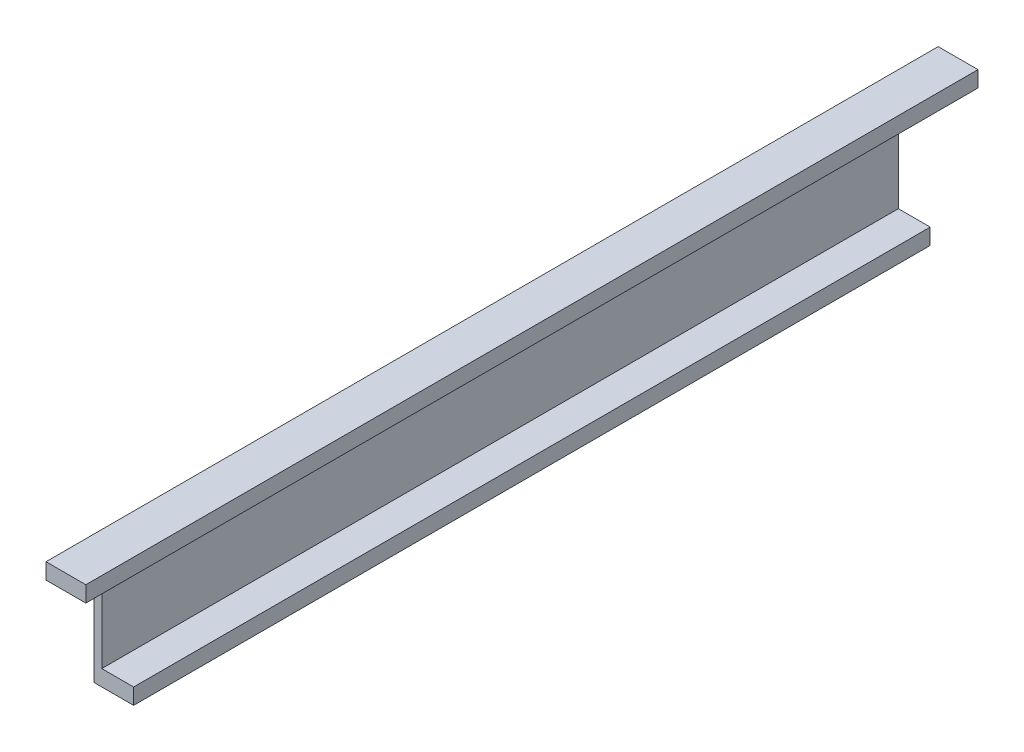
SolidWorks part; units mm, degrees
material "ABS PC"
ref_plane "Alzado" through (0, 0, 0) normal (0, 0, 1) x (1, 0, 0)
ref_plane "Planta" through (0, 0, 0) normal (0, 1, 0) x (1, 0, 0)
ref_plane "Vista lateral" through (0, 0, 0) normal (1, 0, 0) x (0, 0, -1)
sketch "Croquis1" plane through (0, 0, 0) normal (1, 0, 0) x (0, 0, -1)
  line L0 (-110, 24.5) -> (-110, 15) construction
  line L1 (125, -2.5) -> (-125, -2.5)
  line L2 (125, -2.5) -> (125, 2.5)
  line L3 (125, 2.5) -> (-97, 2.5)
  line L4 (-125, -2.5) -> (-125, 2.5)
  line L5 (125, -2.5) -> (0, 0) construction
  line L6 (125, 2.5) -> (-125, -2.5) construction
  line L7 (-117, 17.5) -> (-123, 2.5)
  line L8 (-103, 17.5) -> (-97, 2.5)
  line L9 (-123, 2.5) -> (-125, 2.5)
  circle A0 centre (-110, 17.5) radius 2.5
  arc A1 (-103, 17.5) -> (-117, 17.5) centre (-110, 17.5) ccw
  point P0 (0, 0)
  dimension "D1" = 250
  dimension "D3" = 5
  dimension "D4" = 14
  dimension "D2" = 5
  dimension "D5" = 15
  dimension "D6" = 15
  dimension "D7" = 2
extrude "Saliente-Extruir1" add sketch "Croquis1" along normal mid plane 2.5
sketch "Croquis5" plane through (1.25, 0, 0) normal (1, 0, 0) x (0, 0, -1)
  line L5 (-117, 17.5) -> (-123, 2.5)
  line L6 (-123, 2.5) -> (-125, 2.5)
  line L7 (-125, -2.5) -> (125, -2.5)
  line L8 (125, -2.5) -> (125, 2.5)
  line L9 (-97, 2.5) -> (-103, 17.5)
  line L10 (-117, 17.5) -> (-123, 2.5)
  line L12 (-125, -2.5) -> (125, -2.5)
  line L14 (-97, 2.5) -> (-103, 17.5)
  line L16 (-123, 2.5) -> (-125, 2.5)
  line L17 (-125, 2.5) -> (-125, -2.5)
  line L18 (-125, 2.5) -> (-125, -2.5)
  line L20 (125, -2.5) -> (125, 2.5)
  line L21 (125, 2.5) -> (-97, 2.5)
  line L22 (125, 2.5) -> (-97, 2.5)
  circle A0 centre (-110, 17.5) radius 12.5
  arc A1 (-103, 17.5) -> (-117, 17.5) centre (-110, 17.5) ccw
  arc A2 (-103, 17.5) -> (-117, 17.5) centre (-110, 17.5) ccw
  circle A3 centre (-110, 17.5) radius 15
  dimension "D2" = 25
  dimension "D3" = 30
  dimension "D1" = 0
extrude "Saliente-Extruir4" add sketch "Croquis5" against normal through all contours L14 A3 L10 A0
sketch "Croquis6" plane through (1.25, 0, 0) normal (1, 0, 0) x (0, 0, -1)
  circle A0 centre (-110, 17.5) radius 12.525
  dimension "D1" = 25.05
extrude "Cortar-Extruir3" cut sketch "Croquis6" against normal blind 10
sketch "Croquis7" plane through (0, 0, -125) normal (0, 0, -1) x (-1, 0, 0)
  line L0 (1.25, 32.8) -> (-1.25, 32.8)
  line L1 (1.25, -2.5) -> (3.75, -2.5)
  line L2 (1.25, -2.5) -> (1.25, 2.5) construction
  line L3 (-1.25, 2.5) -> (1.25, 2.5) construction
  line L4 (1.25, -2.5) -> (1.25, 2.5)
  line L5 (-1.25, 2.5) -> (1.25, 2.5)
  line L6 (1.25, 2.5) -> (1.25, 32.8)
  line L7 (1.25, 7.3619) -> (1.25, 32.5) construction
  line L9 (-1.25, 32.8) -> (-1.25, 37.8)
  line L10 (-1.25, 37.8) -> (3.75, 37.8)
  line L11 (3.75, 37.8) -> (3.75, -2.5)
  line M2 (1.25, -2.5) -> (1.25, 2.5)
  dimension "D1" = 30.3
  dimension "D2" = 5
  dimension "D3" = 2.5
extrude "Saliente-Extruir5" add sketch "Croquis7" against normal blind 200 contours L11 L10 L9 L0 L6 L1 M2
sketch "Croquis8" plane through (-1.25, 0, 0) normal (-1, 0, 0) x (0, 0, 1)
  line L0 (97, 2.5) -> (95, 2.5)
  line L1 (75, 2.5) -> (97, 2.5) construction
  line L2 (95, 2.5) -> (95, -2.5)
  line L3 (125, -2.5) -> (75, -2.5) construction
  line L11 (75, 2.5) -> (75, -2.5)
  line L12 (75, -2.5) -> (125, -2.5)
  line L13 (125, -2.5) -> (125, 2.5)
  line L14 (125, 2.5) -> (123, 2.5)
  line L15 (123, 2.5) -> (121.0552, 7.3619)
  line L16 (98.9448, 7.3619) -> (97, 2.5)
  line L17 (97, 2.5) -> (75, 2.5)
  line L18 (75, 2.5) -> (75, -2.5)
  line L19 (75, -2.5) -> (125, -2.5)
  line L20 (125, -2.5) -> (125, 2.5)
  line L21 (125, 2.5) -> (123, 2.5)
  line L22 (123, 2.5) -> (121.0552, 7.3619)
  line L23 (98.9448, 7.3619) -> (97, 2.5)
  line L24 (97, 2.5) -> (75, 2.5)
  circle A0 centre (110, 17.5) radius 12.525 construction
  arc A1 (121.0552, 7.3619) -> (98.9448, 7.3619) centre (110, 17.5) ccw
  arc A2 (121.0552, 7.3619) -> (98.9448, 7.3619) centre (110, 17.5) ccw
  circle A3 centre (110, 17.5) radius 12.525
  circle M2 centre (110, 17.5) radius 12.525
  line M4 (75, -2.5) -> (125, -2.5)
  line M5 (125, -2.5) -> (125, 2.5)
  line M6 (125, 2.5) -> (123, 2.5)
  line M7 (123, 2.5) -> (121.0552, 7.3619)
  arc M8 (121.0552, 7.3619) -> (98.9448, 7.3619) centre (110, 17.5) ccw
  line M9 (98.9448, 7.3619) -> (97, 2.5)
  line M10 (97, 2.5) -> (75, 2.5)
  dimension "D1" = 2
  dimension "D2" = 0
extrude "Saliente-Extruir6" add sketch "Croquis8" along normal blind 21 contours L2 M10 M4 M5 M6 M7 M8 M9 M2
sketch "Croquis10" plane through (0, 0, 75) normal (0, 0, 1) x (1, 0, 0)
  line L0 (1.25, 2.5) -> (1.25, 7.3619) construction
  line L1 (-22.25, 7.3619) -> (-22.25, 2.5) construction
  line L2 (-22.25, 2.5) -> (1.25, 2.5) construction
  line L3 (1.25, 2.5) -> (-22.25, 2.5) construction
  line L4 (-22.25, 2.5) -> (-22.25, -2.5) construction
  line L5 (-22.25, -2.5) -> (1.25, -2.5) construction
  line L6 (1.25, -2.5) -> (1.25, 2.5) construction
  line L7 (-3.75, 37.8) -> (-3.75, -2.5)
  line L8 (-3.75, -2.5) -> (-1.25, -2.5)
  line L9 (-1.25, -2.5) -> (-1.25, 2.5)
  line L10 (-1.25, 2.5) -> (-1.25, 32.8)
  line L11 (-1.25, 32.8) -> (1.25, 32.8)
  line L12 (1.25, 32.8) -> (1.25, 37.8)
  line L13 (1.25, 37.8) -> (-3.75, 37.8)
  line L14 (-3.75, 37.8) -> (-3.75, -2.5)
  line L15 (-3.75, -2.5) -> (-1.25, -2.5)
  line L16 (-1.25, -2.5) -> (-1.25, 2.5)
  line L17 (-1.25, 2.5) -> (-1.25, 32.8)
  line L18 (-1.25, 32.8) -> (1.25, 32.8)
  line L19 (1.25, 32.8) -> (1.25, 37.8)
  line L20 (1.25, 37.8) -> (-3.75, 37.8)
  line L21 (1.25, 7.3619) -> (1.25, 32.5) construction
  line L22 (1.25, 7.3619) -> (-22.25, 7.3619) construction
  line L23 (-22.25, 32.5) -> (-22.25, 7.3619) construction
  line L24 (1.25, 2.5) -> (1.25, 7.3619)
  line L25 (-22.25, 7.3619) -> (-22.25, 2.5)
  line L26 (-22.25, 2.5) -> (1.25, 2.5)
  line L27 (1.25, 2.5) -> (-22.25, 2.5)
  line L28 (-22.25, 2.5) -> (-22.25, -2.5)
  line L29 (-22.25, -2.5) -> (1.25, -2.5)
  line L30 (1.25, -2.5) -> (1.25, 2.5)
  line L31 (1.25, 7.3619) -> (1.25, 32.5)
  line L32 (1.25, 7.3619) -> (-22.25, 7.3619)
  line L33 (-22.25, 32.5) -> (-22.25, 7.3619)
  line L38 (-22.25, 32.5) -> (1.25, 32.5)
  line M8 (-3.75, 37.8) -> (-3.75, -2.5)
  line M9 (-3.75, -2.5) -> (-1.25, -2.5)
  line M10 (-1.25, -2.5) -> (-1.25, 2.5)
  line M11 (-1.25, 2.5) -> (-1.25, 32.8)
  line M12 (-1.25, 32.8) -> (1.25, 32.8)
  line M13 (1.25, 32.8) -> (1.25, 37.8)
  line M14 (1.25, 37.8) -> (-3.75, 37.8)
  dimension "D1" = 0
extrude "Cortar-Extruir5" cut sketch "Croquis10" along normal blind 98 contours L38 L33 L32 L14 | L38 M8 M11 M12 M13 M14 | L38 L17 L32 L31 | L38 L14 L32 L17 | L14 L32 L25 L26 | L32 L14 L26 M11 | L24 L32 L26 M11 | L26 L14 M9 M10 | L28 L29 L14 L26 | L29 L30 L26 M10
sketch "Croquis11" plane through (0, 0, 75) normal (0, 0, 1) x (1, 0, 0)
  line L8 (-3.75, 37.8) -> (-3.75, -2.5)
  line L9 (-3.75, -2.5) -> (1.25, -2.5)
  line L10 (1.25, -2.5) -> (1.25, 2.5)
  line L11 (1.25, 2.5) -> (-1.25, 2.5)
  line L12 (-1.25, 2.5) -> (-1.25, 32.8)
  line L13 (-1.25, 32.8) -> (1.25, 32.8)
  line L14 (1.25, 32.8) -> (1.25, 37.8)
  line L15 (1.25, 37.8) -> (-3.75, 37.8)
  line L16 (-3.75, 37.8) -> (-3.75, -2.5)
  line L17 (-3.75, -2.5) -> (1.25, -2.5)
  line L18 (1.25, -2.5) -> (1.25, 2.5)
  line L19 (1.25, 2.5) -> (-1.25, 2.5)
  line L20 (-1.25, 2.5) -> (-1.25, 32.8)
  line L21 (-1.25, 32.8) -> (1.25, 32.8)
  line L22 (1.25, 32.8) -> (1.25, 37.8)
  line L23 (1.25, 37.8) -> (-3.75, 37.8)
  dimension "D1" = 0
extrude "Saliente-Extruir7" add sketch "Croquis11" along normal blind 50
sketch "Croquis14" plane through (0, 0, 125) normal (0, 0, 1) x (1, 0, 0)
  line L0 (-1.25, 32.8) -> (1.25, 32.8) construction
  line L1 (1.25, 37.8) -> (-3.75, 37.8) construction
  line L2 (1.25, 32.8) -> (1.25, 37.8) construction
  line L3 (-1.25, 32.8) -> (1.25, 32.8)
  line L4 (1.25, 37.8) -> (-3.75, 37.8)
  line L5 (1.25, 32.8) -> (1.25, 37.8)
  line L6 (-1.25, 32.8) -> (-3.75, 32.8)
  line L7 (-3.75, 37.8) -> (-3.75, 32.8)
  line L8 (-3.75, 37.8) -> (-3.75, -2.5) construction
extrude "Saliente-Extruir8" add sketch "Croquis14" along normal blind 15 and the other way blind 265
sketch "Croquis15" plane through (1.25, 0, 0) normal (1, 0, 0) x (0, 0, -1)
  line L0 (125, 2.5) -> (-125, 2.5) construction
  line L1 (-125, 2.5) -> (-125, -2.5) construction
  line L2 (-125, -2.5) -> (125, -2.5) construction
  line L3 (125, -2.5) -> (125, 2.5) construction
  line L4 (-140, 32.8) -> (140, 32.8) construction
  line L5 (140, 32.8) -> (140, 37.8) construction
  line L6 (140, 37.8) -> (-140, 37.8) construction
  line L7 (-140, 37.8) -> (-140, 32.8) construction
  line L8 (125, 2.5) -> (-125, 2.5)
  line L9 (-125, 2.5) -> (-125, -2.5)
  line L10 (-125, -2.5) -> (125, -2.5)
  line L11 (125, -2.5) -> (125, 2.5)
  line L12 (-140, 32.8) -> (140, 32.8)
  line L13 (140, 32.8) -> (140, 37.8)
  line L14 (140, 37.8) -> (-140, 37.8)
  line L15 (-140, 37.8) -> (-140, 32.8)
extrude "Saliente-Extruir9" add sketch "Croquis15" along normal blind 7.5
